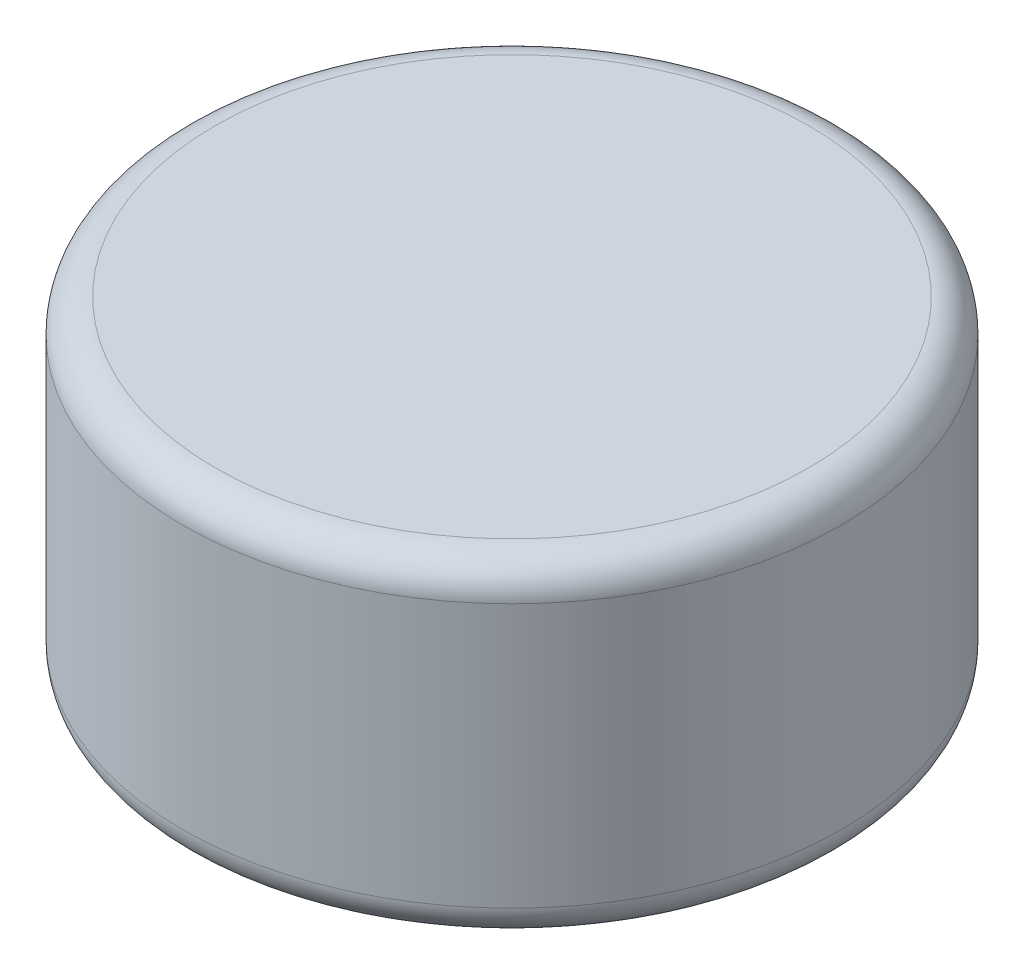
SolidWorks part; units mm, degrees
ref_plane "Front Plane" through (0, 0, 0) normal (0, 0, 1) x (1, 0, 0)
ref_plane "Top Plane" through (0, 0, 0) normal (0, 1, 0) x (1, 0, 0)
ref_plane "Right Plane" through (0, 0, 0) normal (1, 0, 0) x (0, 0, -1)
sketch "Sketch1" plane through (0, 0, 0) normal (0, 1, 0) x (1, 0, 0)
  circle A0 centre (0, 0) radius 2
  dimension "D1" = 4
extrude "Boss-Extrude1" add sketch "Sketch1" along normal blind 2
fillet "Fillet1" radius 0.2 2 edges at (0, 0, 2) (0, 2, 2)
